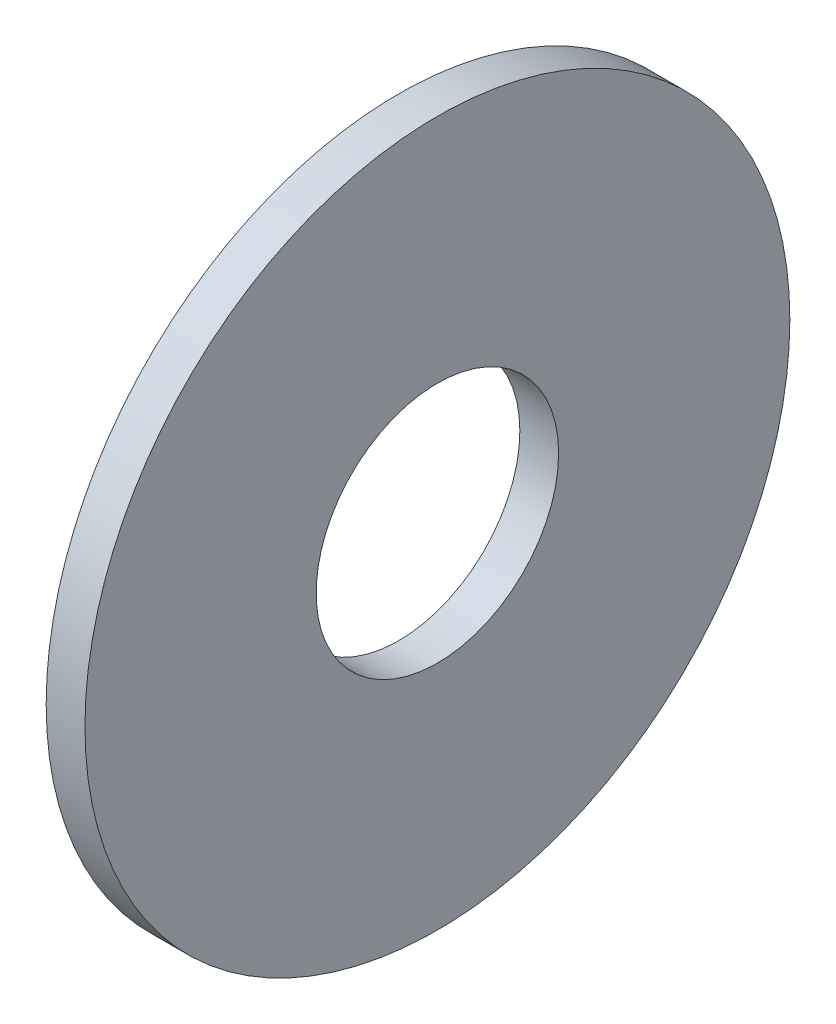
SolidWorks part; units mm, degrees
ref_plane "Front Plane" through (0, 0, 0) normal (0, 0, 1) x (1, 0, 0)
ref_plane "Top Plane" through (0, 0, 0) normal (0, 1, 0) x (1, 0, 0)
ref_plane "Right Plane" through (0, 0, 0) normal (1, 0, 0) x (0, 0, -1)
sketch "Sketch1" plane through (0, 0, 0) normal (1, 0, 0) x (0, 0, -1)
  circle A0 centre (0, 0) radius 12.7
  circle A1 centre (0, 0) radius 4.3688
  dimension "OD" = 25.4
  dimension "ID" = 8.7376
extrude "Boss-Extrude1" add sketch "Sketch1" along normal blind 1.397
